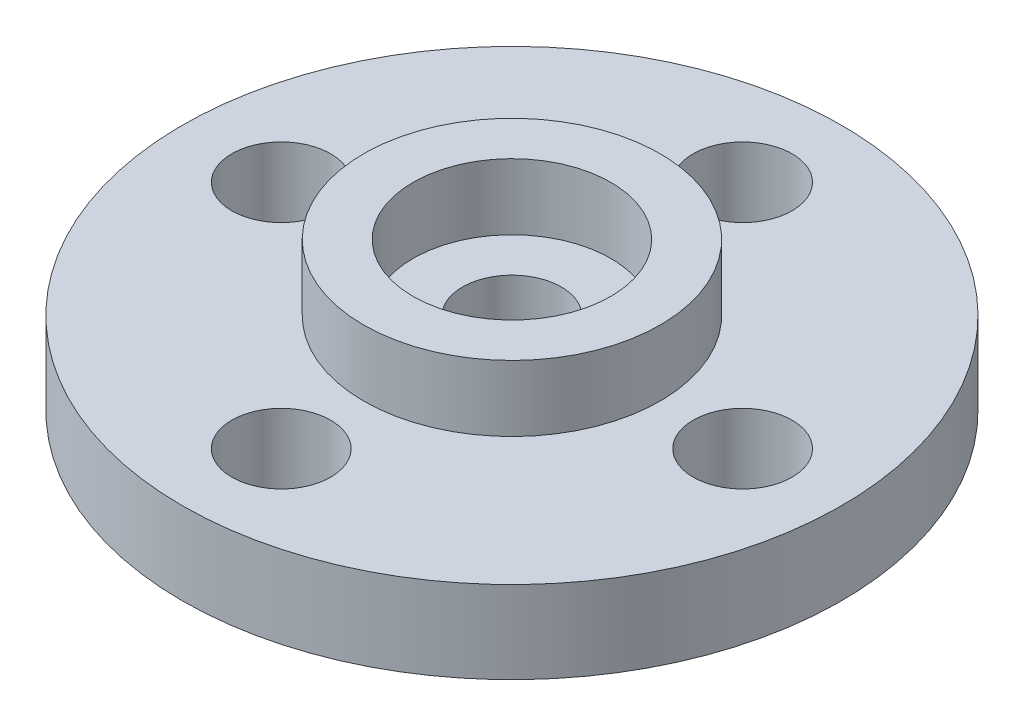
SolidWorks part; units mm, degrees
ref_plane "前视基准面" through (0, 0, 0) normal (0, 0, 1) x (1, 0, 0)
ref_plane "上视基准面" through (0, 0, 0) normal (0, 1, 0) x (1, 0, 0)
ref_plane "右视基准面" through (0, 0, 0) normal (1, 0, 0) x (0, 0, -1)
sketch "草图1" plane through (0, 0, 0) normal (0, 1, 0) x (1, 0, 0)
  circle A0 centre (0, 0) radius 10
  dimension "D1" = 20
extrude "凸台-拉伸1" add sketch "草图1" along normal blind 2.5
sketch "草图2" plane through (0, 2.5, 0) normal (0, 1, 0) x (1, 0, 0)
  circle A0 centre (0, 7) radius 1.5
  circle A1 centre (7, 0) radius 1.5
  circle A2 centre (0, -7) radius 1.5
  circle A3 centre (-7, 0) radius 1.5
  point P12 (0, 0)
  dimension "D1" = 3
  dimension "D2" = 7
  dimension "D3" = 4
extrude "切除-拉伸1" cut sketch "草图2" against normal through all
sketch "草图3" plane through (0, 2.5, 0) normal (0, 1, 0) x (1, 0, 0)
  circle A0 centre (0, 0) radius 4.5
  dimension "D1" = 9
extrude "凸台-拉伸2" add sketch "草图3" along normal blind 2
sketch "草图4" plane through (0, 4.5, 0) normal (0, 1, 0) x (1, 0, 0)
  circle A0 centre (0, 0) radius 3
  dimension "D1" = 6
extrude "切除-拉伸2" cut sketch "草图4" against normal blind 2
sketch "草图5" plane through (0, 2.5, 0) normal (0, 1, 0) x (1, 0, 0)
  circle A0 centre (0, 0) radius 1.5
  dimension "D1" = 3
extrude "切除-拉伸3" cut sketch "草图5" against normal through all
